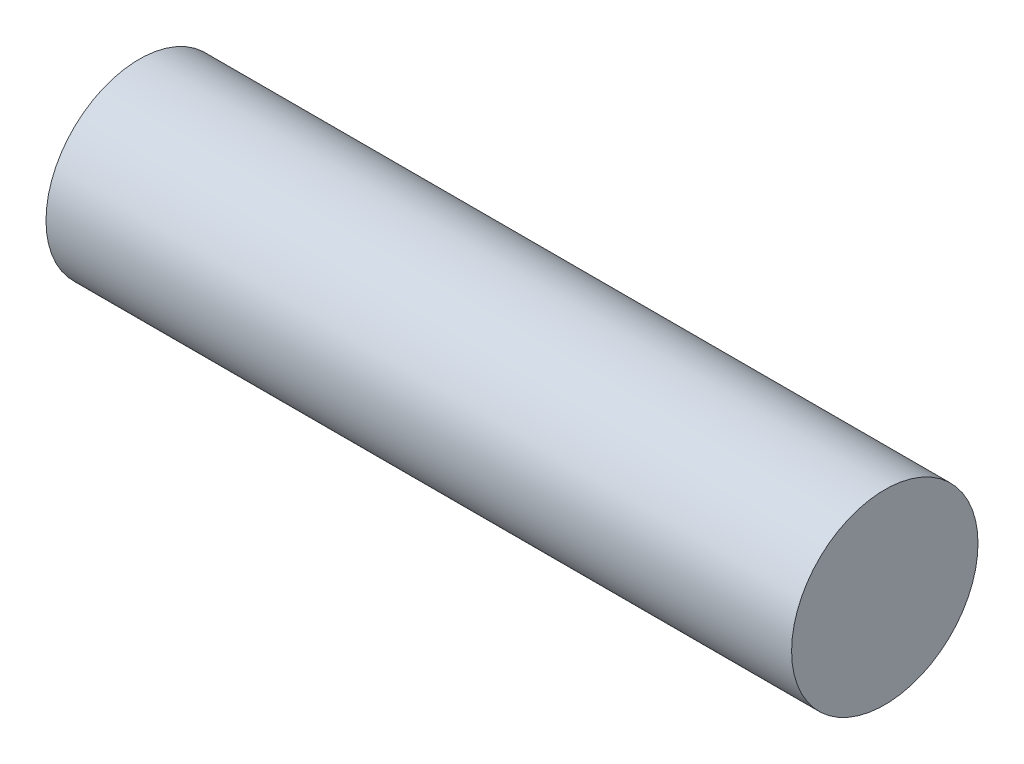
SolidWorks part; units mm, degrees
ref_plane "Front Plane" through (0, 0, 0) normal (0, 0, 1) x (1, 0, 0)
ref_plane "Top Plane" through (0, 0, 0) normal (0, 1, 0) x (1, 0, 0)
ref_plane "Right Plane" through (0, 0, 0) normal (1, 0, 0) x (0, 0, -1)
sketch "Sketch1" plane through (0, 0, 0) normal (0, 0, 1) x (1, 0, 0)
  line L0 (0, 0) -> (-27.6323, 0) construction
  line L1 (0, 0) -> (20, 0)
  line L2 (0, 0) -> (0, 3.75)
  line L3 (0, 3.75) -> (20, 3.75)
  line L4 (20, 0) -> (20, 3.75)
  dimension "D1" = 7.5
  dimension "D2" = 20
revolve "Revolve1" add sketch "Sketch1" angle 360 about L0
sketch "Sketch2" plane through (0, 0, 0) normal (-1, 0, 0) x (0, 0, 1)
  line L0 (0, -3.75) -> (0, 3.75) construction
  line L1 (-3.375, 1.125) -> (-1.125, 1.125)
  line L2 (-3.375, 1.125) -> (-3.375, -1.125)
  line L3 (-3.375, -1.125) -> (-1.125, -1.125)
  line L4 (3.375, 1.125) -> (3.375, -1.125)
  line L5 (-1.125, 3.375) -> (1.125, 3.375)
  line L6 (-1.125, 3.375) -> (-1.125, 1.125)
  line L7 (-1.125, -3.375) -> (1.125, -3.375)
  line L8 (1.125, 3.375) -> (1.125, 1.125)
  line L9 (-3.75, 0) -> (3.75, 0) construction
  line L10 (1.125, -1.125) -> (3.375, -1.125)
  line L11 (1.125, -1.125) -> (1.125, -3.375)
  line L12 (-1.125, -1.125) -> (-1.125, -3.375)
  line L13 (1.125, 1.125) -> (3.375, 1.125)
  circle A0 centre (0, 0) radius 3.75 construction
  point P15 (0, 0)
  point P20 (0, 0)
  dimension "D1" = 7.5
  dimension "D2" = 6.75
extrude "Boss-Extrude1" [suppressed] add sketch "Sketch2" along normal blind 10
sketch "Sketch4" plane through (0, 0, 0) normal (-1, 0, 0) x (0, 0, 1)
  circle A0 centre (0, 0) radius 5.25
  dimension "D1" = 10.5
extrude "Boss-Extrude3" [suppressed] add sketch "Sketch4" against normal blind 2.5
sketch "Sketch3" plane through (0, 0, 0) normal (-1, 0, 0) x (0, 0, 1)
  circle A0 centre (0, 0) radius 3.75
  circle A1 centre (0, 0) radius 3.75 construction
extrude "Boss-Extrude2" add sketch "Sketch3" along normal blind 10
